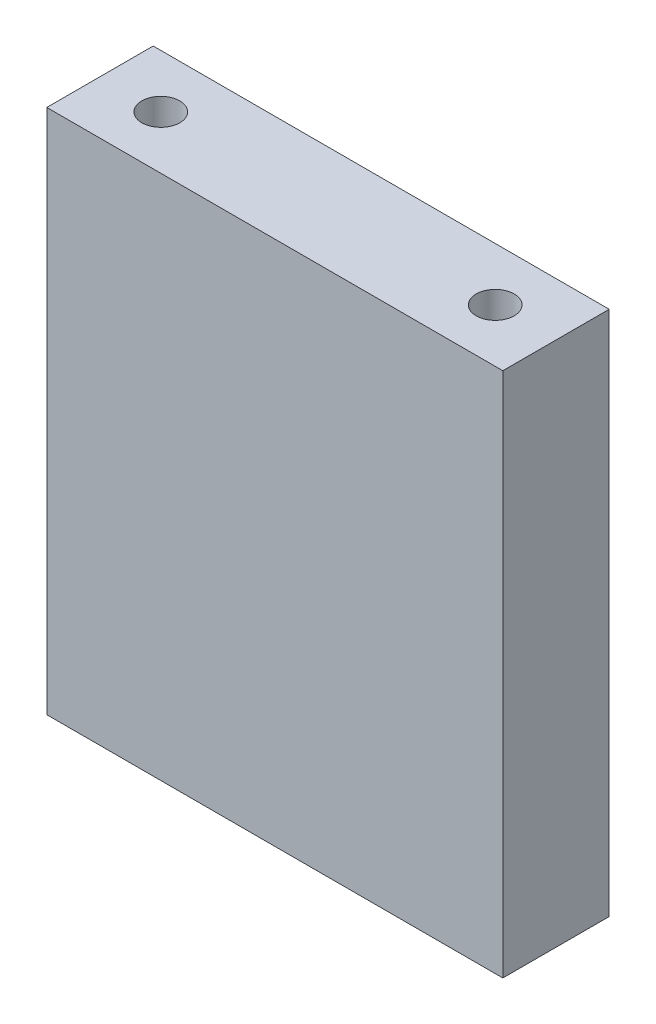
SolidWorks part; units mm, degrees
ref_plane "Спереди" through (0, 0, 0) normal (0, 0, 1) x (1, 0, 0)
ref_plane "Сверху" through (0, 0, 0) normal (0, 1, 0) x (1, 0, 0)
ref_plane "Справа" through (0, 0, 0) normal (1, 0, 0) x (0, 0, -1)
sketch "Эскиз1" plane through (0, 0, 0) normal (0, 0, 1) x (1, 0, 0)
  line L1 (0, 0) -> (30, 0)
  line L2 (0, 0) -> (0, 34.6)
  line L3 (0, 34.6) -> (30, 34.6)
  line L4 (30, 0) -> (30, 34.6)
  dimension "D1" = 34.6
  dimension "D2" = 30
extrude "Бобышка-Вытянуть1" add sketch "Эскиз1" along normal blind 7
sketch "Эскиз2" plane through (0, 34.6, 0) normal (0, 1, 0) x (1, 0, 0)
  line L1 (0, -7) -> (0, 0) construction
  line L2 (30, -7) -> (0, -7) construction
  circle A0 centre (4, -3.5) radius 1.25
  circle A1 centre (26, -3.5) radius 1.25
  point P4 (0, -3.5)
  point P7 (15, -7)
  dimension "D1" = 2.5
  dimension "D2" = 0
  dimension "D3" = 11
  dimension "D5" = 22
  dimension "D4" = 2
extrude "Вырез-Вытянуть1" cut sketch "Эскиз2" against normal through all
